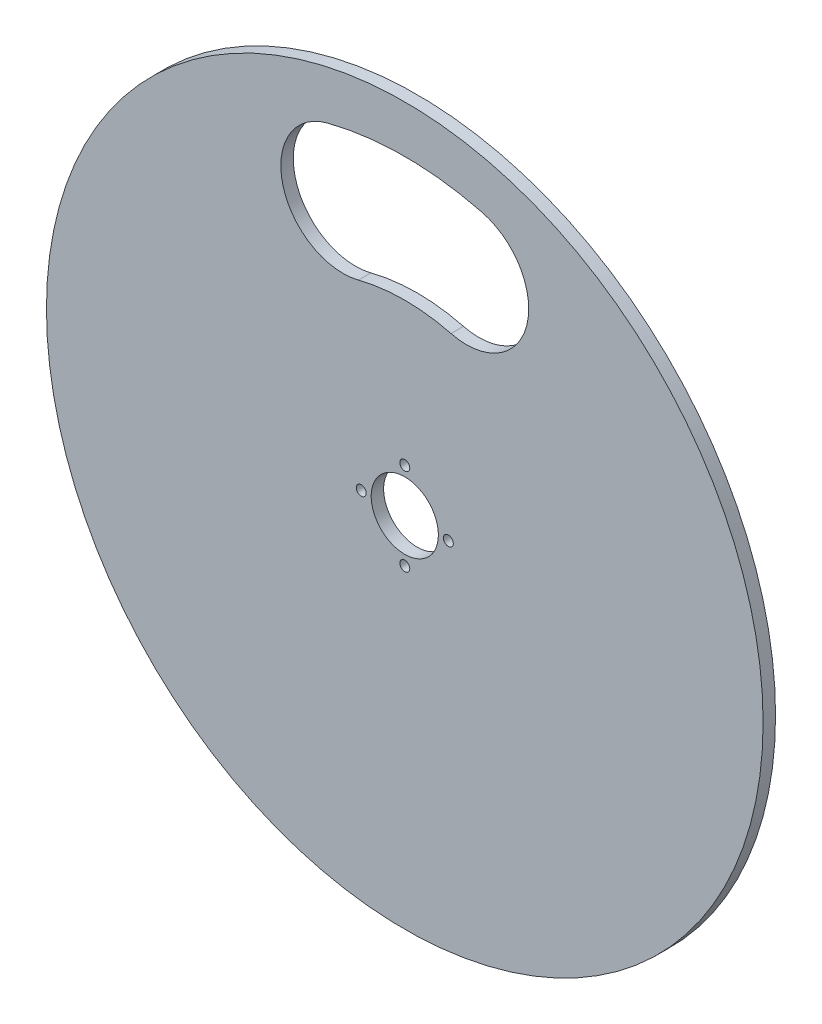
SolidWorks part; units mm, degrees
ref_plane "前视基准面" through (0, 0, 0) normal (0, 0, 1) x (1, 0, 0)
ref_plane "上视基准面" through (0, 0, 0) normal (0, 1, 0) x (1, 0, 0)
ref_plane "右视基准面" through (0, 0, 0) normal (1, 0, 0) x (0, 0, -1)
sketch "草图1" plane through (0, 0, 0) normal (0, 0, 1) x (1, 0, 0)
  arc A1 (0, -13.5) -> (0, 13.5) centre (0, 0) ccw construction
  arc A2 (0, 144) -> (0, -144) centre (0, 0) ccw
  arc A3 (0, -144) -> (0, 144) centre (0, 0) ccw
  arc A4 (0, 144) -> (0, -144) centre (0, 0) ccw
  arc A5 (0, -144) -> (0, 144) centre (0, 0) ccw
  arc A6 (0, 13.5) -> (0, -13.5) centre (0, 0) ccw construction
  arc A7 (17.5, -2) -> (17.5, 2) centre (17.5, 0) ccw construction
  arc A8 (17.5, 2) -> (17.5, -2) centre (17.5, 0) ccw construction
  arc A9 (0, -19.5) -> (0, -15.5) centre (0, -17.5) ccw construction
  arc A10 (0, -15.5) -> (0, -19.5) centre (0, -17.5) ccw construction
  arc A11 (-15.5, 0) -> (-19.5, 0) centre (-17.5, 0) ccw construction
  arc A12 (-17.5, -2) -> (-17.5, 2) centre (-17.5, 0) ccw construction
  arc A13 (-17.5, 2) -> (-17.5, -2) centre (-17.5, 0) ccw construction
  arc A14 (0, 15.5) -> (0, 19.5) centre (0, 17.5) ccw construction
  arc A15 (0, 19.5) -> (0, 15.5) centre (0, 17.5) ccw construction
  arc A16 (0, 19.5) -> (0, 15.5) centre (0, 17.5) ccw
  arc A17 (0, 15.5) -> (0, 19.5) centre (0, 17.5) ccw
  arc A18 (-17.5, 2) -> (-17.5, -2) centre (-17.5, 0) ccw
  arc A19 (-17.5, -2) -> (-17.5, 2) centre (-17.5, 0) ccw
  arc A20 (-15.5, 0) -> (-19.5, 0) centre (-17.5, 0) ccw
  arc A21 (0, -15.5) -> (0, -19.5) centre (0, -17.5) ccw
  arc A22 (0, -19.5) -> (0, -15.5) centre (0, -17.5) ccw
  arc A23 (17.5, 2) -> (17.5, -2) centre (17.5, 0) ccw
  arc A24 (17.5, -2) -> (17.5, 2) centre (17.5, 0) ccw
  arc A25 (0, 13.5) -> (0, -13.5) centre (0, 0) ccw
  arc A26 (0, -13.5) -> (0, 13.5) centre (0, 0) ccw
  arc A27 (31.0049, 121.0938) -> (-31.0049, 121.0937) centre (0, 0) ccw construction
  arc A28 (-31.0049, 121.0937) -> (-24.8039, 71.875) centre (-24.8039, 96.875) ccw construction
  arc A29 (-24.8039, 71.875) -> (-18.6029, 72.6562) centre (-24.8039, 96.875) ccw construction
  arc A30 (24.8039, 71.875) -> (31.0049, 121.0938) centre (24.8039, 96.875) ccw construction
  arc A31 (18.6029, 72.6563) -> (24.8039, 71.875) centre (24.8039, 96.875) ccw construction
  arc A32 (18.6029, 72.6563) -> (-18.6029, 72.6562) centre (0, 0) ccw construction
  arc A33 (24.8039, 71.875) -> (31.0049, 121.0938) centre (24.8039, 96.875) ccw
  arc A34 (18.6029, 72.6563) -> (24.8039, 71.875) centre (24.8039, 96.875) ccw
  arc A35 (18.6029, 72.6563) -> (-18.6029, 72.6562) centre (0, 0) ccw
  arc A36 (-24.8039, 71.875) -> (-18.6029, 72.6562) centre (-24.8039, 96.875) ccw
  arc A37 (-31.0049, 121.0937) -> (-24.8039, 71.875) centre (-24.8039, 96.875) ccw
  arc A38 (31.0049, 121.0938) -> (-31.0049, 121.0937) centre (0, 0) ccw
  dimension "D1" = 0
extrude "凸台-拉伸1" add sketch "草图1" along normal blind 5 contours A4 A5 A38 A33 A34 A35 A36 A37 A26 A25 A24 A23 A22 A21 A19 A18 A17 A16
